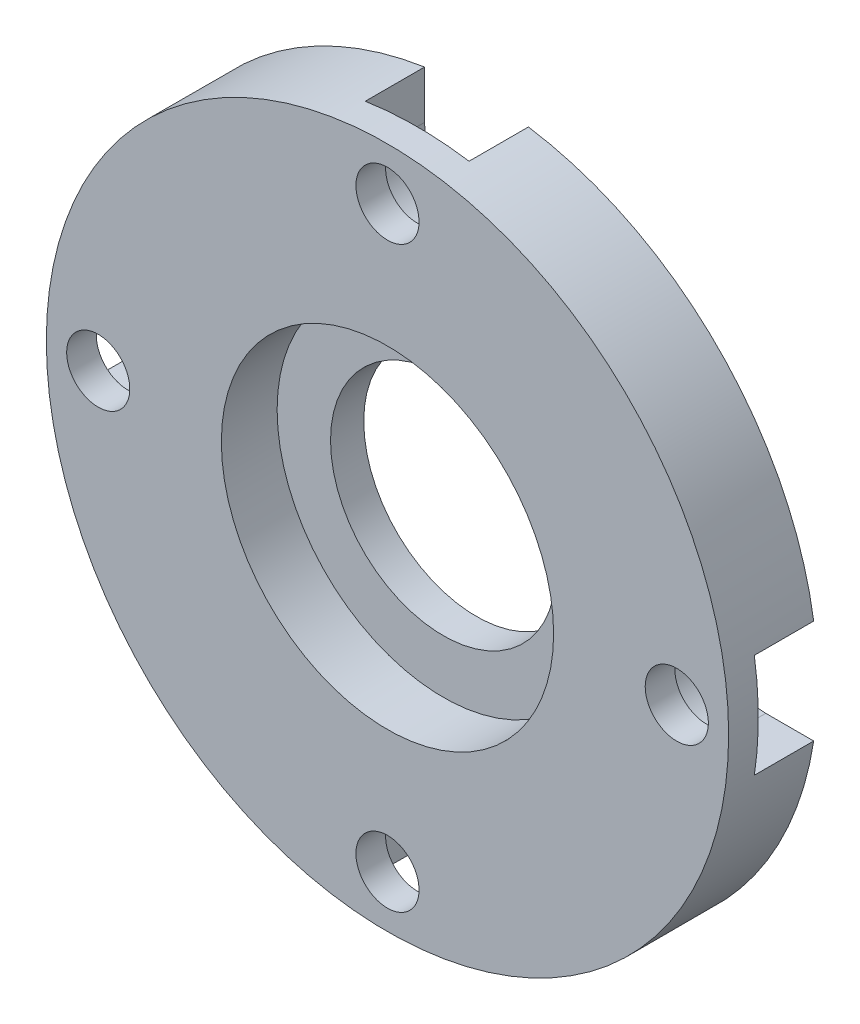
SolidWorks part; units mm, degrees
material "6061-T6 (SS)"
ref_plane "Front Plane" through (0, 0, 0) normal (0, 0, 1) x (1, 0, 0)
ref_plane "Top Plane" through (0, 0, 0) normal (0, 1, 0) x (1, 0, 0)
ref_plane "Right Plane" through (0, 0, 0) normal (1, 0, 0) x (0, 0, -1)
sketch "Derived Main Sketch" plane through (0, 0, 0) normal (1, 0, 0) x (0, 0, -1)
  line L0 (141.5523, 0) -> (-87.5573, 0)
  line L1 (83.82, 36.5125) -> (0, 36.5125) construction
  line L2 (83.82, 36.5125) -> (83.82, -36.5125) construction
  line L3 (83.82, -36.5125) -> (0, -36.5125) construction
  line L4 (0, 36.5125) -> (0, -36.5125) construction
  line L5 (0, 36.5125) -> (-15.24, 36.5125) construction
  line L6 (0, 36.5125) -> (0, -36.5125) construction
  line L7 (0, -36.5125) -> (-15.24, -36.5125) construction
  line L8 (-15.24, 36.5125) -> (-15.24, -36.5125) construction
  line L9 (-25.4, 9.525) -> (0, 9.525)
  line L10 (-25.4, 9.525) -> (-25.4, -9.525)
  line L11 (-25.4, -9.525) -> (0, -9.525)
  line L12 (0, 9.525) -> (0, -9.525)
  line L13 (22, 10.0076) -> (10, 10.0076)
  line L14 (22, 10.0076) -> (22, -10.0076)
  line L15 (22, -10.0076) -> (10, -10.0076)
  line L16 (10, 10.0076) -> (10, -10.0076)
  line L17 (67.945, 9.9949) -> (55.945, 9.9949)
  line L18 (67.945, 9.9949) -> (67.945, -9.9949)
  line L19 (67.945, -9.9949) -> (55.945, -9.9949)
  line L20 (55.945, 9.9949) -> (55.945, -9.9949)
  line L22 (55.945, 9.9949) -> (22, 9.9949)
  line L23 (55.945, 9.9949) -> (55.945, -9.9949)
  line L24 (55.945, -9.9949) -> (22, -9.9949)
  line L25 (22, 9.9949) -> (22, -9.9949)
  line L26 (67.945, 9.525) -> (91.059, 9.525)
  line L27 (67.945, 9.525) -> (67.945, -9.525)
  line L28 (67.945, -9.525) -> (91.059, -9.525)
  line L29 (91.059, 9.525) -> (91.059, -9.525)
  line L30 (103.378, 7.9375) -> (100.838, 7.9375)
  line L31 (103.378, 7.9375) -> (103.378, -7.9375)
  line L32 (103.378, -7.9375) -> (100.838, -7.9375)
  line L33 (100.838, 7.9375) -> (100.838, -7.9375)
  line L34 (10, 12.5) -> (0, 12.5)
  line L35 (10, 12.5) -> (10, -12.5)
  line L36 (10, -12.5) -> (0, -12.5)
  line L37 (0, 12.5) -> (0, -12.5)
  line L38 (-44.4, 7.0002) -> (-29.4, 7.0002)
  line L39 (-44.4, 7.0002) -> (-44.4, -7.0002)
  line L40 (-44.4, -7.0002) -> (-29.4, -7.0002)
  line L41 (-29.4, 7.0002) -> (-29.4, -7.0002)
  line L42 (83.82, 36.5125) -> (93.345, 36.5125) construction
  line L43 (83.82, 36.5125) -> (83.82, -36.5125) construction
  line L44 (83.82, -36.5125) -> (93.345, -36.5125) construction
  line L45 (93.345, 36.5125) -> (93.345, -36.5125) construction
  line L46 (103.378, -7.9375) -> (91.059, -7.9375)
  line L47 (103.378, -7.9375) -> (103.378, 7.9375)
  line L48 (103.378, 7.9375) -> (91.059, 7.9375)
  line L49 (91.059, -7.9375) -> (91.059, 7.9375)
  line L54 (-25.4, 7.5) -> (-29.4, 7.5)
  line L55 (-25.4, 7.5) -> (-25.4, -7.5)
  line L56 (-25.4, -7.5) -> (-29.4, -7.5)
  line L57 (-29.4, 7.5) -> (-29.4, -7.5)
  line L58 (103.378, 3.8989) -> (131.445, 3.8989)
  line L59 (103.378, 3.8989) -> (103.378, -3.8989)
  line L60 (103.378, -3.8989) -> (131.445, -3.8989)
  line L61 (131.445, 3.8989) -> (131.445, -3.8989)
  point P66 (-22.86, -7.5)
sketch "Cap" plane through (0, 0, 0) normal (1, 0, 0) x (0, 0, -1)
  line L0 (83.82, 36.5125) -> (83.82, -36.5125) construction
  line L1 (83.82, 36.5125) -> (93.345, 36.5125) construction
  line L2 (93.345, 36.5125) -> (93.345, -36.5125) construction
  line L3 (103.378, 7.9375) -> (91.059, 7.9375) construction
  line L4 (83.82, 36.5125) -> (83.82, -36.5125) construction
  line L5 (83.82, 36.5125) -> (93.345, 36.5125) construction
  line L6 (93.345, 36.5125) -> (93.345, -36.5125) construction
  line L7 (103.378, 7.9375) -> (91.059, 7.9375)
  line L8 (200141.5523, 0) -> (-200087.5573, 0) construction
  line L9 (200141.5523, 0) -> (-200087.5573, 0)
  line L10 (-1000, 0) -> (49000, 0)
  line L11 (93.345, 12.065) -> (89.789, 12.065)
  line L12 (89.789, 12.065) -> (89.789, 17.78)
  line L13 (89.789, 17.78) -> (83.82, 17.78)
  line L14 (83.82, 17.78) -> (83.82, 36.5125) construction
  line L15 (93.345, 36.5125) -> (93.345, 12.065) construction
  line L16 (93.345, 36.5125) -> (83.82, 36.5125) construction
  line L17 (93.345, 12.065) -> (93.345, 36.5125)
  line L18 (93.345, 36.5125) -> (83.82, 36.5125)
  line L19 (83.82, 36.5125) -> (83.82, 17.78)
  dimension "D1" = 12.065
  dimension "D2" = 17.78
  dimension "D3" = 3.556
revolve "Endcap-Revolve" add sketch "Cap" angle 360 about L0
sketch "Bolt Locations" plane through (0, 0, -93.345) normal (0, 0, -1) x (-1, 0, 0)
  circle A0 centre (0, 0) radius 30.9575 construction
  point P3 (0, 30.9575)
  point P4 (30.9575, 0)
  point P5 (0, -30.9575)
  point P6 (-30.9575, 0)
  dimension "D1" = 61.915
hole_wizard "CBORE for 1/4 Socket Head Cap Screw1" positions "Sketch4" profile "Sketch5" counterbore size "1/4" standard "ANSI Inch" end condition through all
sketch "Sketch4" plane through (0, 0, -93.345) normal (0, 0, -1) x (-1, 0, 0)
  point P0 (0, 30.9575)
  point P3 (30.9575, 0)
  point P6 (0, -30.9575)
  point P9 (-30.9575, 0)
sketch "Sketch5" plane through (0, 30.9575, -93.345) normal (1, 0, 0) x (0, 1, 0)
  line L0 (0, 0) -> (0, 9.525)
  line L1 (0, 9.525) -> (3.3782, 9.525)
  line L3 (3.3782, 9.525) -> (3.3782, 6.35)
  line L4 (3.3782, 6.35) -> (5.5562, 6.35)
  line L5 (5.5562, 6.35) -> (5.5562, 0)
  line L7 (5.5562, 0) -> (0, 0)
  line L11 (0, -6.35) -> (0, 107.95) construction
  dimension "Thru Hole Dia." = 6.7564
  dimension "Thru Hole Depth" = 9.525
  dimension "C'Bore Dia." = 11.1125
  dimension "C'Bore Depth" = 6.35
sketch "Bolt-Clearance" plane through (0, 0, -93.345) normal (0, 0, -1) x (-1, 0, 0)
  line L0 (5.5562, 30.9575) -> (5.5562, 37.3075)
  line L1 (5.5562, 37.3075) -> (-5.5562, 37.3075)
  line L2 (-5.5562, 37.3075) -> (-5.5562, 30.9575)
  line L3 (0, 30.9575) -> (5.5562, 30.9575)
  line L4 (0, 30.9575) -> (-5.5562, 30.9575)
  line L5 (30.9575, 0) -> (30.9575, 5.5562)
  line L6 (37.3075, 5.5562) -> (30.9575, 5.5562)
  line L7 (37.3075, -5.5563) -> (37.3075, 5.5562)
  line L8 (30.9575, -5.5563) -> (37.3075, -5.5563)
  line L9 (30.9575, 0) -> (30.9575, -5.5563)
  line L10 (0, -30.9575) -> (5.5563, -30.9575)
  line L11 (5.5563, -37.3075) -> (5.5563, -30.9575)
  line L12 (-5.5562, -37.3075) -> (5.5563, -37.3075)
  line L13 (-5.5562, -30.9575) -> (-5.5562, -37.3075)
  line L14 (0, -30.9575) -> (-5.5562, -30.9575)
  line L15 (-30.9575, 0) -> (-30.9575, -5.5563)
  line L16 (-37.3075, -5.5563) -> (-30.9575, -5.5563)
  line L17 (-37.3075, 5.5562) -> (-37.3075, -5.5563)
  line L18 (-30.9575, 5.5562) -> (-37.3075, 5.5562)
  line L19 (-30.9575, 0) -> (-30.9575, 5.5562)
  line L20 (0, 0) -> (0, 30.9575) construction
  arc A0 (-0.129, 36.5123) -> (0.129, 36.5123) centre (0, 30.9575) ccw construction
  arc A1 (-0.129, 36.5123) -> (0.129, 36.5123) centre (0, 30.9575) ccw construction
  dimension "D1" = 6.35
  dimension "D3" = 30.9575
  dimension "D2" = 4
extrude "Cut-Extrude1" cut sketch "Bolt-Clearance" against normal up to surface (6.35 mm away) contours L1 L2 L4 L3 L0 | L5 L6 L7 L8 L9 | L10 L11 L12 L13 L14 | L15 L16 L17 L18 L19 up to face at (0, 30.9569, -86.995)
equation "\"D2@Cap\"=1.4 / 2"
